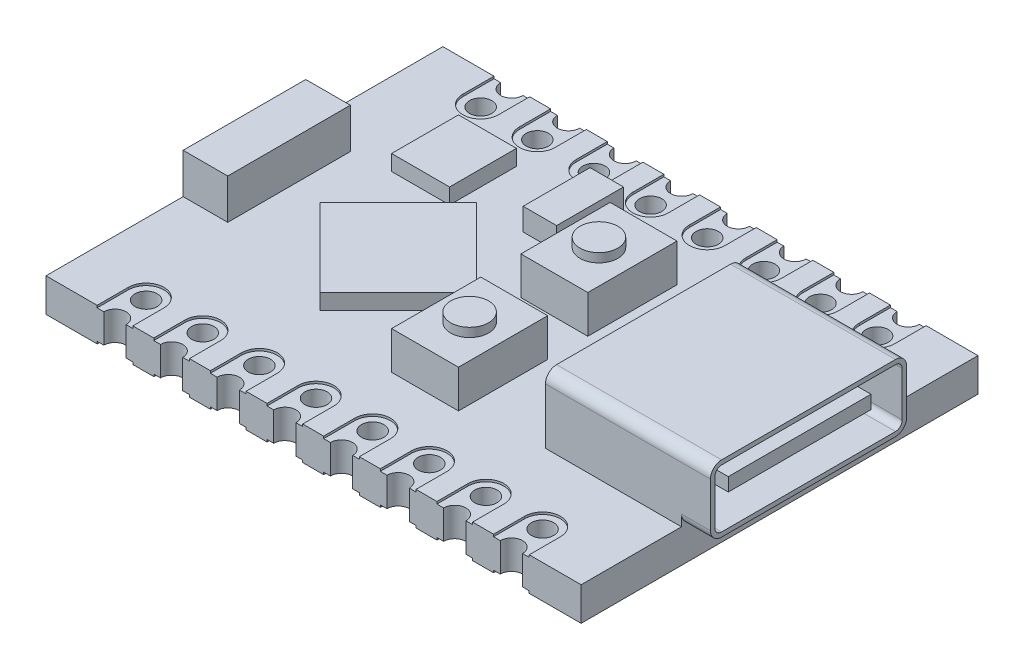
SolidWorks part; units mm, degrees
ref_plane "Front Plane" through (0, 0, 0) normal (0, 0, 1) x (1, 0, 0)
ref_plane "Top Plane" through (0, 0, 0) normal (0, 1, 0) x (1, 0, 0)
ref_plane "Right Plane" through (0, 0, 0) normal (1, 0, 0) x (0, 0, -1)
sketch "Sketch1" plane through (0, 0, 0) normal (0, 1, 0) x (1, 0, 0)
  line L1 (0, 0) -> (24, 0)
  line L2 (0, 0) -> (0, 17.8)
  line L3 (0, 17.8) -> (24, 17.8)
  line L4 (24, 0) -> (24, 17.8)
  dimension "D1" = 24
  dimension "D2" = 17.8
sketch "Sketch2" plane through (0, 0, 0) normal (0, 1, 0) x (1, 0, 0)
  line L0 (0, 0) -> (0, 17.8) construction
  line L1 (0, 0) -> (0, 17.8)
  line L2 (0, 17.8) -> (24, 17.8) construction
  line L3 (0, 17.8) -> (24, 17.8)
  line L4 (24, 0) -> (24, 17.8) construction
  line L5 (24, 0) -> (24, 17.8)
  line L6 (0, 0) -> (24, 0) construction
  line L7 (0, 0) -> (24, 0)
extrude "Boss-Extrude1" add sketch "Sketch2" against normal blind 1.5
sketch "Sketch3" plane through (0, 0, 0) normal (0, 1, 0) x (1, 0, 0)
  line L0 (0, 8.9) -> (24, 8.9) construction
  line L1 (0, 0) -> (0, 17.8) construction
  line L2 (24, 0) -> (24, 17.8) construction
  line L4 (2, 11.65) -> (0, 11.65)
  line L5 (2, 11.65) -> (2, 6.15)
  line L6 (2, 6.15) -> (0, 6.15)
  line L7 (0, 11.65) -> (0, 6.15)
  line L8 (2, 11.65) -> (0, 6.15) construction
  line L9 (2, 6.15) -> (0, 11.65) construction
  point P6 (1, 8.9)
  dimension "D1" = 5.5
  dimension "D2" = 2
extrude "Boss-Extrude2" add sketch "Sketch3" along normal blind 1.8
sketch "Sketch4" plane through (0, 0, 0) normal (0, 1, 0) x (1, 0, 0)
  line L0 (2, 6.15) -> (2, 11.65) construction
  line L3 (4, 8.3) -> (7.5, 11.8)
  line L4 (4, 8.3) -> (7.5, 4.8)
  line L5 (7.5, 11.8) -> (11, 8.3)
  line L6 (7.5, 4.8) -> (11, 8.3)
  line L7 (0, 17.8) -> (24, 17.8) construction
  point P0 (4.1289, 8.4029)
  point P6 (0, 0)
  point P11 (0, 0)
  point P12 (0, 0)
  dimension "D1" = 6
  dimension "D2" = 7
  dimension "D3" = 7
  dimension "D4" = 2
extrude "Boss-Extrude3" add sketch "Sketch4" along normal blind 0.7
sketch "Sketch5" plane through (0, 0, 0) normal (0, 1, 0) x (1, 0, 0)
  line L0 (0, 17.8) -> (24, 17.8) construction
  line L1 (3.7, 14.8) -> (6.3, 14.8)
  line L2 (3.7, 14.8) -> (3.7, 11.8)
  line L3 (3.7, 11.8) -> (6.3, 11.8)
  line L4 (6.3, 14.8) -> (6.3, 11.8)
  line L5 (0, 0) -> (0, 17.8) construction
  dimension "D1" = 2.6
  dimension "D2" = 3
  dimension "D3" = 3
  dimension "D4" = 3.7
extrude "Boss-Extrude4" add sketch "Sketch5" along normal blind 0.7
sketch "Sketch6" plane through (0, 0, 0) normal (0, 1, 0) x (1, 0, 0)
  line L0 (0, 0) -> (0, 17.8) construction
  line L1 (9, 15.4) -> (10.5, 15.4)
  line L2 (9, 15.4) -> (9, 12.4)
  line L3 (9, 12.4) -> (10.5, 12.4)
  line L4 (10.5, 15.4) -> (10.5, 12.4)
  line L5 (0, 17.8) -> (24, 17.8) construction
  dimension "D1" = 1.5
  dimension "D2" = 3
  dimension "D3" = 9
  dimension "D4" = 2.4
extrude "Boss-Extrude5" add sketch "Sketch6" along normal blind 1
sketch "Sketch7" plane through (0, 0, 0) normal (0, 1, 0) x (1, 0, 0)
  line L0 (0, 17.8) -> (24, 17.8) construction
  line L1 (11.5, 13.8) -> (14.5, 13.8)
  line L2 (11.5, 13.8) -> (11.5, 9.8)
  line L3 (11.5, 9.8) -> (14.5, 9.8)
  line L4 (14.5, 13.8) -> (14.5, 9.8)
  line L6 (24, 0) -> (24, 17.8) construction
  dimension "D1" = 3
  dimension "D2" = 4
  dimension "D3" = 4
  dimension "D4" = 9.5
extrude "Boss-Extrude6" add sketch "Sketch7" along normal blind 1.7
sketch "Sketch8" plane through (0, 1.7, 0) normal (0, 1, 0) x (1, 0, 0)
  line L0 (13, 11.8) -> (13, 13.8) construction
  line L1 (14.5, 13.8) -> (11.5, 13.8) construction
  line L2 (13, 11.8) -> (11.5, 11.8) construction
  line L3 (11.5, 13.8) -> (11.5, 9.8) construction
  circle A0 centre (13, 11.8) radius 0.85
  dimension "D1" = 1.7
extrude "Boss-Extrude7" add sketch "Sketch8" along normal blind 0.4
ref_plane "Plane1" through (0, 0, -8.9) normal (0, 0, -1) x (-1, 0, 0)
mirror "Mirror1" about plane through (0, 0, -8.9) normal (0, 0, -1) of "Boss-Extrude7", "Boss-Extrude6"
sketch "Sketch9" plane through (0, 0, 0) normal (0, 1, 0) x (1, 0, 0)
  line L0 (3.0931, 16.4027) -> (0, 16.4027) construction
  line L1 (0, 0) -> (0, 17.8) construction
  line L2 (0, 16.4027) -> (24, 16.4027) construction
  line L3 (24, 0) -> (24, 17.8) construction
  circle A0 centre (3.0931, 16.4027) radius 0.5
  circle A1 centre (5.6331, 16.4027) radius 0.5
  circle A2 centre (8.1731, 16.4027) radius 0.5
  circle A3 centre (10.7131, 16.4027) radius 0.5
  circle A4 centre (13.2531, 16.4027) radius 0.5
  circle A5 centre (15.7931, 16.4027) radius 0.5
  circle A6 centre (18.3331, 16.4027) radius 0.5
  circle A7 centre (20.8731, 16.4027) radius 0.5
  dimension "D1" = 1
  dimension "D2" = 8
extrude "Cut-Extrude1" cut sketch "Sketch9" against normal through all
sketch "Sketch10" plane through (0, 0, 0) normal (0, 1, 0) x (1, 0, 0)
  line L0 (2.2931, 16.4027) -> (2.2931, 17.8)
  line L1 (0, 17.8) -> (24, 17.8) construction
  line L2 (3.8931, 16.4027) -> (3.8931, 17.8)
  line L3 (3.8931, 17.8) -> (2.2931, 17.8)
  circle A0 centre (3.0931, 16.4027) radius 0.5 construction
  circle A1 centre (3.0931, 16.4027) radius 0.5 construction
  arc A2 (2.2931, 16.4027) -> (3.8931, 16.4027) centre (3.0931, 16.4027) ccw
  circle A3 centre (3.0931, 17.8) radius 0.5 construction
  circle A4 centre (3.0931, 16.4027) radius 0.8 construction
  dimension "D2" = 1
  dimension "D1" = 0.3
extrude "Cut-Extrude2" cut sketch "Sketch10" against normal blind 0.1
pattern_linear "LPattern1" count 8 spacing 2.54 along (1, 0, 0) of "Cut-Extrude2"
sketch "Sketch11" plane through (0, 0, 0) normal (0, 1, 0) x (1, 0, 0)
  circle A0 centre (3.0931, 17.8) radius 0.5 construction
  circle A1 centre (3.0931, 17.8) radius 0.5
  circle A2 centre (5.6331, 17.8) radius 0.5
  circle A3 centre (8.1731, 17.8) radius 0.5
  circle A4 centre (10.7131, 17.8) radius 0.5
  circle A5 centre (13.2531, 17.8) radius 0.5
  circle A6 centre (15.7931, 17.8) radius 0.5
  circle A7 centre (18.3331, 17.8) radius 0.5
  circle A8 centre (20.8731, 17.8) radius 0.5
  dimension "D1" = 8
extrude "Cut-Extrude3" cut sketch "Sketch11" against normal through all
ref_plane "Plane2" through (0, -0.75, 0) normal (0, 1, 0) x (1, 0, 0)
mirror "Mirror2" about plane through (0, -0.75, 0) normal (0, 1, 0) of "LPattern1", "Cut-Extrude2"
mirror "Mirror3" about plane through (0, 0, -8.9) normal (0, 0, -1) of "Cut-Extrude3", "Mirror2", "LPattern1", "Cut-Extrude2", "Cut-Extrude1"
ref_plane "Plane3" through (25.3, 0, 0) normal (1, 0, 0) x (0, 0, -1)
sketch "Sketch12" plane through (25.3, 0, 0) normal (1, 0, 0) x (0, 0, -1)
  line L0 (8.9, 0) -> (8.9, 3) construction
  line L1 (0, 0) -> (17.8, 0) construction
  line L2 (4.5, 1.5) -> (13.3, 1.5) construction
  line L4 (4.5, 3) -> (13.3, 3)
  line L5 (4.5, 3) -> (4.5, 0)
  line L6 (4.5, 0) -> (13.3, 0)
  line L7 (13.3, 3) -> (13.3, 0)
  line L8 (4.5, 3) -> (13.3, 0) construction
  line L9 (4.5, 0) -> (13.3, 3) construction
  point P4 (8.9, 1.5)
  point P7 (8.9, 1.5)
  point P12 (0, 0)
  dimension "D1" = 3
  dimension "D2" = 8.8
extrude "Boss-Extrude8" add sketch "Sketch12" against normal blind 7.4
fillet "Fillet1" radius 0.5 4 edges at (24.65, 0, -4.5) (24.65, 0, -13.3) (21.6, 3, -13.3) (21.6, 3, -4.5)
sketch "Sketch13" plane through (25.3, 0, 0) normal (1, 0, 0) x (0, 0, -1)
  line L0 (4.7, 2.5) -> (4.7, 0.5)
  line L1 (5, 0.2) -> (12.8, 0.2)
  line L2 (13.1, 0.5) -> (13.1, 2.5)
  line L3 (12.8, 2.8) -> (5, 2.8)
  line L4 (4.5, 2.5) -> (4.5, 0.5)
  line L5 (5, 0) -> (12.8, 0)
  line L6 (13.3, 0.5) -> (13.3, 2.5)
  line L7 (12.8, 3) -> (5, 3)
  line L8 (4.5, 2.5) -> (4.5, 0.5)
  line L9 (5, 0) -> (12.8, 0)
  line L10 (13.3, 0.5) -> (13.3, 2.5)
  line L11 (12.8, 3) -> (5, 3)
  arc A0 (5, 2.8) -> (4.7, 2.5) centre (5, 2.5) ccw
  arc A1 (4.7, 0.5) -> (5, 0.2) centre (5, 0.5) ccw
  arc A2 (12.8, 0.2) -> (13.1, 0.5) centre (12.8, 0.5) ccw
  arc A3 (13.1, 2.5) -> (12.8, 2.8) centre (12.8, 2.5) ccw
  arc A4 (4.5, 0.5) -> (5, 0) centre (5, 0.5) ccw
  arc A5 (12.8, 0) -> (13.3, 0.5) centre (12.8, 0.5) ccw
  arc A6 (13.3, 2.5) -> (12.8, 3) centre (12.8, 2.5) ccw
  arc A7 (5, 3) -> (4.5, 2.5) centre (5, 2.5) ccw
  arc A8 (4.5, 0.5) -> (5, 0) centre (5, 0.5) ccw
  arc A9 (12.8, 0) -> (13.3, 0.5) centre (12.8, 0.5) ccw
  arc A10 (13.3, 2.5) -> (12.8, 3) centre (12.8, 2.5) ccw
  arc A11 (5, 3) -> (4.5, 2.5) centre (5, 2.5) ccw
  dimension "D1" = 0
  dimension "D2" = 0.2
extrude "Cut-Extrude4" cut sketch "Sketch13" against normal blind 6.4 contours L2 A3 L3 A0 L0 A1 L1 A2
sketch "Sketch14" plane through (18.9, 0, 0) normal (1, 0, 0) x (0, 0, -1)
  line L0 (5.7, 1.8) -> (5.7, 1.2)
  line L1 (5.7, 1.2) -> (12.1, 1.2)
  line L2 (12.1, 1.2) -> (12.1, 1.8)
  line L3 (12.1, 1.8) -> (5.7, 1.8)
  line L4 (13.1, 0.5) -> (13.1, 2.5)
  line L5 (12.8, 2.8) -> (5, 2.8)
  line L6 (4.7, 2.5) -> (4.7, 0.5)
  line L7 (5, 0.2) -> (12.8, 0.2)
  line L8 (13.1, 0.5) -> (13.1, 2.5)
  line L9 (12.8, 2.8) -> (5, 2.8)
  line L10 (4.7, 2.5) -> (4.7, 0.5)
  line L11 (5, 0.2) -> (12.8, 0.2)
  arc A0 (5.7, 1.8) -> (5.7, 1.8) centre (5.7, 1.8) ccw
  arc A1 (5.7, 1.2) -> (5.7, 1.2) centre (5.7, 1.2) ccw
  arc A2 (12.1, 1.2) -> (12.1, 1.2) centre (12.1, 1.2) ccw
  arc A3 (12.1, 1.8) -> (12.1, 1.8) centre (12.1, 1.8) ccw
  arc A4 (13.1, 2.5) -> (12.8, 2.8) centre (12.8, 2.5) ccw
  arc A5 (5, 2.8) -> (4.7, 2.5) centre (5, 2.5) ccw
  arc A6 (4.7, 0.5) -> (5, 0.2) centre (5, 0.5) ccw
  arc A7 (12.8, 0.2) -> (13.1, 0.5) centre (12.8, 0.5) ccw
  arc A8 (13.1, 2.5) -> (12.8, 2.8) centre (12.8, 2.5) ccw
  arc A9 (5, 2.8) -> (4.7, 2.5) centre (5, 2.5) ccw
  arc A10 (4.7, 0.5) -> (5, 0.2) centre (5, 0.5) ccw
  arc A11 (12.8, 0.2) -> (13.1, 0.5) centre (12.8, 0.5) ccw
  dimension "D1" = 0
  dimension "D2" = 1
extrude "Boss-Extrude9" add sketch "Sketch14" along normal blind 6 contours L2 L3 L0 L1
sketch "Sketch15" plane through (0, 0, 0) normal (-1, 0, 0) x (0, 0, 1)
  line L0 (-6.15, 1.8) -> (-6.15, 0) construction
  line L1 (-11.65, 0) -> (-6.15, 0)
  line L2 (-11.65, 0) -> (-11.65, 0.01)
  line L3 (-11.65, 0.01) -> (-6.15, 0.01)
  line L4 (-6.15, 0) -> (-6.15, 0.01)
  dimension "D1" = 0.01
extrude "Cut-Extrude5" cut sketch "Sketch15" against normal blind 0.01
